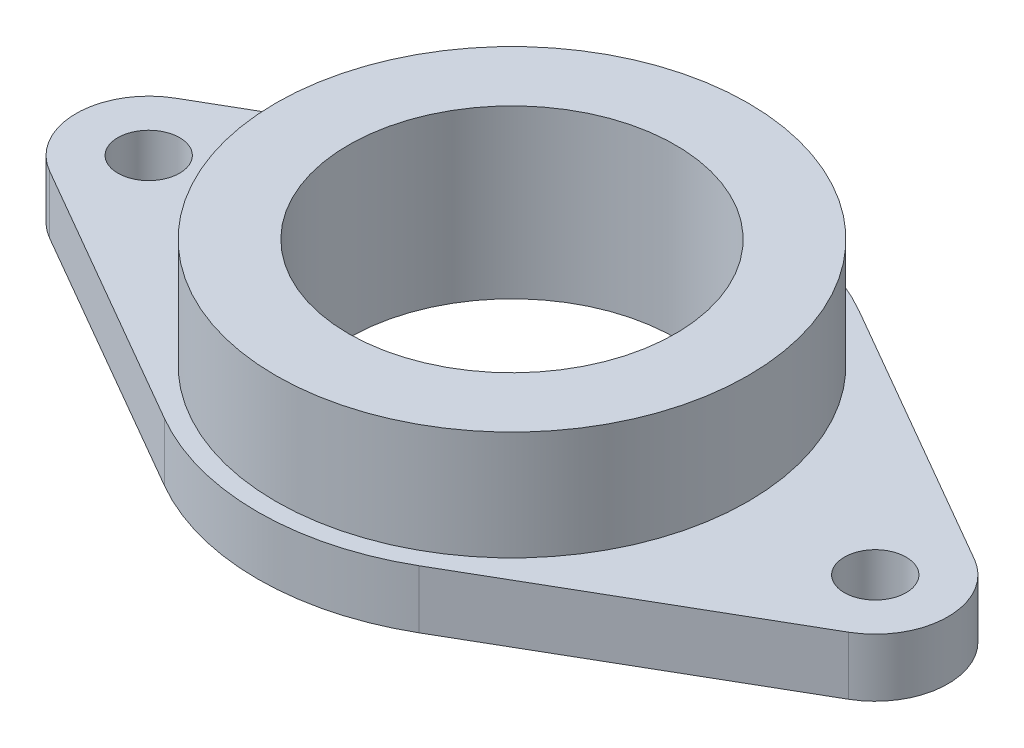
SolidWorks part; units mm, degrees
material "AISI 1010 Steel, hot rolled bar"
ref_plane "Front Plane" through (0, 0, 0) normal (0, 0, 1) x (1, 0, 0)
ref_plane "Top Plane" through (0, 0, 0) normal (0, 1, 0) x (1, 0, 0)
ref_plane "Right Plane" through (0, 0, 0) normal (1, 0, 0) x (0, 0, -1)
sketch "Sketch1" plane through (0, 0, 0) normal (0, 1, 0) x (1, 0, 0)
  line L0 (0, 0) -> (0, 64.158) construction
  line L1 (-55, 8.6603) -> (-17.5, 30.3109)
  line L2 (-55, -8.6603) -> (-17.5, -30.3109)
  line L3 (55, -8.6603) -> (17.5, -30.3109)
  line L4 (55, 8.6603) -> (17.5, 30.3109)
  arc A0 (-17.5, -30.3109) -> (17.5, -30.3109) centre (0, 0) ccw
  arc A1 (-55, 8.6603) -> (-55, -8.6603) centre (-50, 0) ccw
  circle A2 centre (-50, 0) radius 4.25
  circle A3 centre (50, 0) radius 4.25
  arc A4 (55, 8.6603) -> (55, -8.6603) centre (50, 0) cw
  arc A5 (17.5, 30.3109) -> (-17.5, 30.3109) centre (0, 0) ccw
  circle A6 centre (0, 0) radius 22.5
  dimension "D1" = 70
  dimension "D2" = 20
  dimension "D3" = 8.5
  dimension "D4" = 50
  dimension "D5" = 45
extrude "Boss-Extrude1" add sketch "Sketch1" along normal blind 23
sketch "Sketch2" plane through (0, 23, 0) normal (0, 1, 0) x (1, 0, 0)
  circle A0 centre (0, 0) radius 32.5
  dimension "D1" = 65
extrude "Cut-Extrude1" cut sketch "Sketch2" against normal blind 15 flip side to cut
